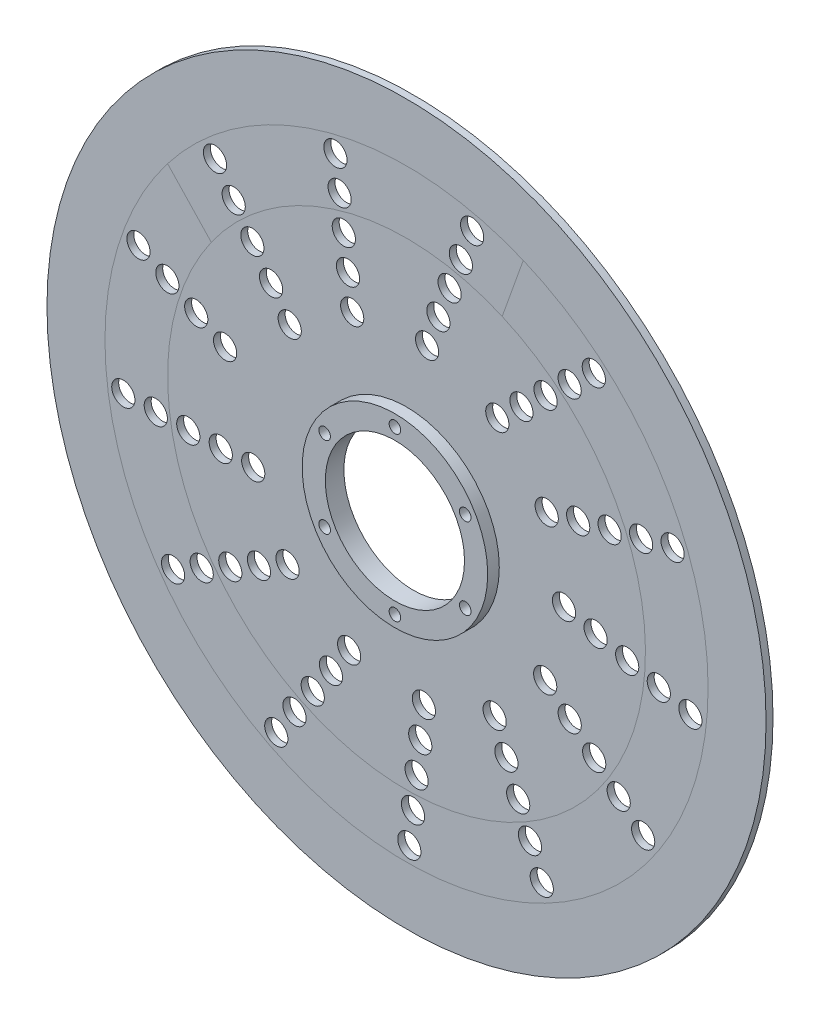
SolidWorks part; units mm, degrees
ref_plane "Front Plane" through (0, 0, 0) normal (0, 0, 1) x (1, 0, 0)
ref_plane "Top Plane" through (0, 0, 0) normal (0, 1, 0) x (1, 0, 0)
ref_plane "Right Plane" through (0, 0, 0) normal (1, 0, 0) x (0, 0, -1)
sketch "Sketch1" plane through (0, 0, 0) normal (0, 0, 1) x (1, 0, 0)
  circle A0 centre (0, 0) radius 30
extrude "Extrude-Thin1" add sketch "Sketch1" along normal blind 3 thin
sketch "Sketch3" plane through (0, 0, 3) normal (0, 0, 1) x (1, 0, 0)
  circle A0 centre (0, 0) radius 30
extrude "Extrude-Thin2" add sketch "Sketch3" along normal blind 5 thin
sketch "Sketch7" plane through (0, 0, 3) normal (0, 0, 1) x (1, 0, 0)
  circle A6 centre (-50.3512, 45.5418) radius 5
  circle A7 centre (-58.4026, 56.9949) radius 5
  circle A8 centre (-66.4541, 68.448) radius 5
  circle A9 centre (-74.5056, 79.9012) radius 5
  circle A10 centre (-82.557, 91.3543) radius 5
  circle A14 centre (-23.4194, 63.7246) radius 5
  circle A15 centre (-25.2261, 77.6076) radius 5
  circle A16 centre (-27.0328, 91.4905) radius 5
  circle A17 centre (-28.8395, 105.3734) radius 5
  circle A18 centre (-30.6462, 119.2564) radius 5
  circle A22 centre (8.8774, 67.3089) radius 5
  circle A23 centre (13.7294, 80.4412) radius 5
  circle A24 centre (18.5814, 93.5736) radius 5
  circle A25 centre (23.4334, 106.7059) radius 5
  circle A26 centre (28.2854, 119.8383) radius 5
  circle A30 centre (39.1406, 55.4735) radius 5
  circle A31 centre (49.5397, 64.8468) radius 5
  circle A32 centre (59.9388, 74.2201) radius 5
  circle A33 centre (70.3379, 83.5934) radius 5
  circle A34 centre (80.7371, 92.9666) radius 5
  circle A38 centre (60.4371, 30.9298) radius 5
  circle A39 centre (74.001, 34.3967) radius 5
  circle A40 centre (87.565, 37.8637) radius 5
  circle A41 centre (101.1289, 41.3306) radius 5
  circle A42 centre (114.6929, 44.7975) radius 5
  circle A46 centre (67.8882, -0.6995) radius 5
  circle A47 centre (81.5096, -3.9332) radius 5
  circle A48 centre (95.1311, -7.1669) radius 5
  circle A49 centre (108.7525, -10.4005) radius 5
  circle A50 centre (122.3739, -13.6342) radius 5
  circle A54 centre (59.7869, -32.1686) radius 5
  circle A55 centre (70.3453, -41.3621) radius 5
  circle A56 centre (80.9038, -50.5556) radius 5
  circle A57 centre (91.4622, -59.749) radius 5
  circle A58 centre (102.0206, -68.9425) radius 5
  circle A62 centre (37.9892, -56.2683) radius 5
  circle A63 centre (43.0658, -69.3154) radius 5
  circle A64 centre (48.1424, -82.3626) radius 5
  circle A65 centre (53.219, -95.4097) radius 5
  circle A66 centre (58.2956, -108.4569) radius 5
  circle A70 centre (7.4886, -67.4775) radius 5
  circle A71 centre (5.9204, -81.3894) radius 5
  circle A72 centre (4.3522, -95.3013) radius 5
  circle A73 centre (2.7839, -109.2132) radius 5
  circle A74 centre (1.2157, -123.1251) radius 5
  circle A78 centre (-24.7276, -63.2285) radius 5
  circle A79 centre (-32.5813, -74.8181) radius 5
  circle A80 centre (-40.4351, -86.4077) radius 5
  circle A81 centre (-48.2888, -97.9973) radius 5
  circle A82 centre (-56.1426, -109.5868) radius 5
  circle A86 centre (-51.2789, -44.4946) radius 5
  circle A87 centre (-63.619, -51.1068) radius 5
  circle A88 centre (-75.9591, -57.7191) radius 5
  circle A89 centre (-88.2992, -64.3313) radius 5
  circle A90 centre (-100.6394, -70.9436) radius 5
  circle A94 centre (-66.0829, -15.5675) radius 5
  circle A95 centre (-80.0824, -15.6876) radius 5
  circle A96 centre (-94.0819, -15.8077) radius 5
  circle A97 centre (-108.0814, -15.9278) radius 5
  circle A98 centre (-122.0808, -16.048) radius 5
  circle A103 centre (-78.1998, 23.3254) radius 5
  circle A104 centre (-90.6516, 29.725) radius 5
  circle A105 centre (-103.1033, 36.1245) radius 5
  circle A106 centre (-115.5551, 42.524) radius 5
  circle A125 centre (-65.7481, 16.9259) radius 5 [skipped]
  dimension "D2" = 13
extrude "Cut-Extrude3" cut sketch "Sketch7" against normal through all
sketch "Sketch8" plane through (0, 0, 8) normal (0, 0, 1) x (1, 0, 0)
  line L0 (0, 30) -> (0, 40)
  circle A5 centre (0, 0) radius 30 construction
  circle A6 centre (0, 0) radius 30 construction
  circle A7 centre (0, 0) radius 40 construction
sketch "Sketch9" plane through (0, 0, 8) normal (0, 0, 1) x (1, 0, 0)
  line L0 (0, 30) -> (0, 40) construction
  circle A0 centre (0, 35) radius 2.5
  circle A1 centre (30.3109, 17.5) radius 2.5
  circle A2 centre (30.3109, -17.5) radius 2.5
  circle A3 centre (0, -35) radius 2.5
  circle A4 centre (-30.3109, -17.5) radius 2.5
  circle A5 centre (-30.3109, 17.5) radius 2.5
  point P16 (0, 0)
extrude "Cut-Extrude4" cut sketch "Sketch9" against normal through all
sketch "Sketch10" plane through (0, 0, 3) normal (0, 0, 1) x (1, 0, 0)
  circle A0 centre (0, 0) radius 103
  circle A1 centre (0, 0) radius 130
split line "Split Line1"
sketch "Sketch11" plane through (0, 0, 3) normal (0, 0, 1) x (1, 0, 0)
  line L1 (50.3336, 119.8605) -> (41.2368, 94.385)
  line L2 (-103, 79.3158) -> (-84.1693, 59.3677)
  circle A0 centre (0, 0) radius 103 construction
  circle A1 centre (0, 0) radius 130 construction
  circle A2 centre (0, 0) radius 103 construction
  circle A3 centre (0, 0) radius 130 construction
  dimension "D1" = 63
split line "Split Line2"
sketch "Sketch12" plane through (0, 0, 0) normal (0, 0, -1) x (-1, 0, 0)
  circle A0 centre (0, 2.7523) radius 126.8662
  circle A1 centre (0, 0) radius 104.2487
split line "Split Line12"
sketch "Sketch14" plane through (0, 0, 0) normal (0, 0, -1) x (-1, 0, 0)
  line L0 (-41.2368, 94.385) -> (-50.3336, 119.8605)
  line L1 (103, 79.3158) -> (84.1693, 59.3677)
  arc A1 (-50.3336, 119.8605) -> (103, 79.3158) centre (-0.5254, -1.9871) cw
  arc A2 (-41.2368, 94.385) -> (84.1693, 59.3677) centre (0.8462, 3.0304) cw
split line "Split Line15"
